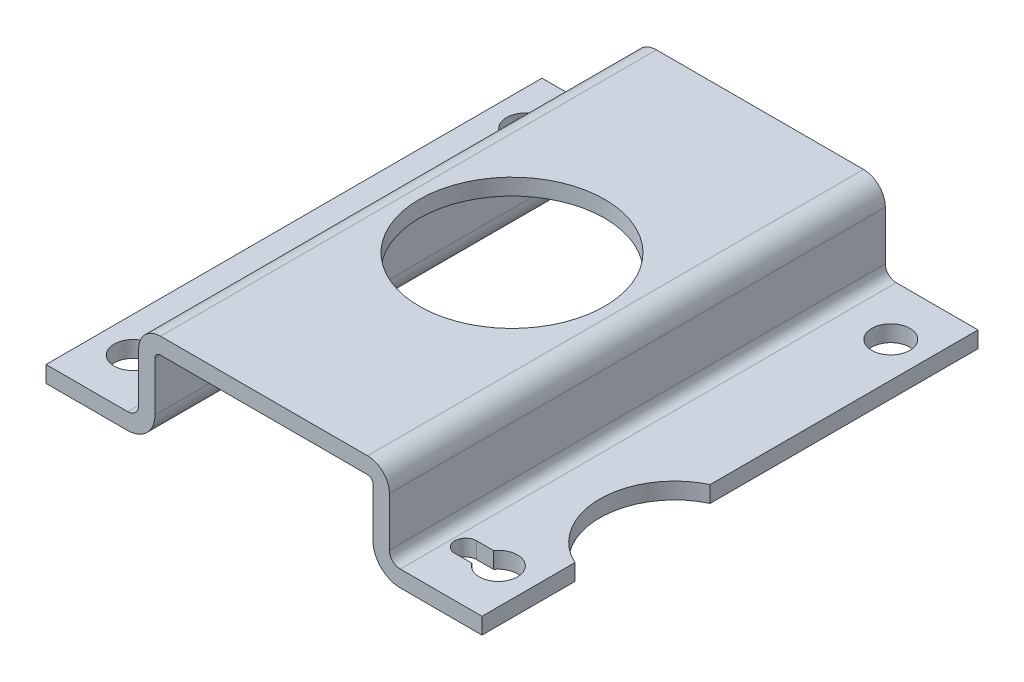
SolidWorks part; units mm, degrees
material "AISI 1010 钢，热轧条材"
ref_plane "前视基准面" through (0, 0, 0) normal (0, 0, 1) x (1, 0, 0)
ref_plane "上视基准面" through (0, 0, 0) normal (0, 1, 0) x (1, 0, 0)
ref_plane "右视基准面" through (0, 0, 0) normal (1, 0, 0) x (0, 0, -1)
sketch "草图1" plane through (0, 0, 0) normal (0, 0, 1) x (1, 0, 0)
  line L0 (0, 0) -> (0, 50000) construction
  line L1 (0, 18) -> (-23, 18)
  line L2 (-40, 0) -> (-40, 3)
  line L3 (0, 15) -> (-20, 15)
  line L4 (-40, 3) -> (-23, 3)
  line L5 (-23, 3) -> (-23, 18)
  line L6 (-20, 0) -> (-20, 15)
  line L7 (-40, 0) -> (-20, 0)
  line L8 (-37.0264, 0) -> (-37.0264, 0)
  line L9 (-40, 0.3974) -> (-40, 3) construction
  line L10 (-37.0264, 0) -> (-20, 0) construction
  line L11 (0, 0) -> (50000, 0) construction
  line L12 (40, 0) -> (20, 0)
  line L13 (20, 0) -> (20, 15)
  line L14 (23, 3) -> (23, 18)
  line L15 (40, 3) -> (23, 3)
  line L16 (0, 15) -> (20, 15)
  line L17 (40, 0) -> (40, 3)
  line L18 (0, 18) -> (23, 18)
  dimension "D2" = 46
  dimension "D3" = 80
  dimension "D4" = 18
  dimension "D1" = 3
extrude "凸台-拉伸1" add sketch "草图1" along normal mid plane 91 contours L3 L6 L7 L2 L4 L5 L1 L18 L14 L15 L17 L12 L13 L16
fillet "圆角1" radius 4 2 edges at (23, 18, 0) (-23, 18, 0)
fillet "圆角2" radius 1 2 edges at (20, 15, 0) (-20, 15, 0)
fillet "圆角3" radius 5 2 edges at (20, 0, 0) (-20, 0, 0)
fillet "圆角4" radius 2 2 edges at (23, 3, 0) (-23, 3, 0)
sketch "草图2" plane through (0, 0, 0) normal (0, -1, 0) x (1, 0, 0)
  line L0 (-27.5, 38) -> (-30.6277, 38)
  line L1 (-33.5, -36) -> (33.5, -36) construction
  line L2 (-33.5, -36) -> (-33.5, 36) construction
  line L3 (-33.5, 36) -> (33.5, 36) construction
  line L4 (33.5, -36) -> (33.5, 36) construction
  line L5 (-33.5, -36) -> (33.5, 36) construction
  line L6 (-33.5, 36) -> (33.5, -36) construction
  line L7 (-27.5, 34) -> (-30.6277, 34)
  line L8 (0, 0) -> (0, 50000) construction
  line L9 (27.5, 34) -> (30.6277, 34)
  line L10 (27.5, 38) -> (30.6277, 38)
  arc A0 (-30.6277, 38) -> (-30.6277, 34) centre (-33.5, 36) ccw
  circle A1 centre (-33.5, -36) radius 3.5
  arc A2 (30.6277, 34) -> (30.6277, 38) centre (33.5, 36) ccw
  circle A3 centre (33.5, -36) radius 3.5
  arc A4 (-27.5, 34) -> (-27.5, 38) centre (-27.5, 36) ccw
  arc A5 (27.5, 34) -> (27.5, 38) centre (27.5, 36) cw
  point P0 (0, 0)
  dimension "D3" = 7
  dimension "D4" = 4
  dimension "D5" = 6
  dimension "D1" = 72
  dimension "D2" = 67
extrude "切除-拉伸1" cut sketch "草图2" against normal blind 10
sketch "草图3" plane through (0, 0, 0) normal (0, -1, 0) x (1, 0, 0)
  circle A0 centre (45.9254, 16.0657) radius 13.7609
extrude "切除-拉伸2" cut sketch "草图3" against normal blind 10
sketch "草图4" plane through (0, 18, 0) normal (0, 1, 0) x (1, 0, 0)
  circle A0 centre (0, 0) radius 17
  dimension "D1" = 34
extrude "切除-拉伸3" cut sketch "草图4" against normal blind 10
